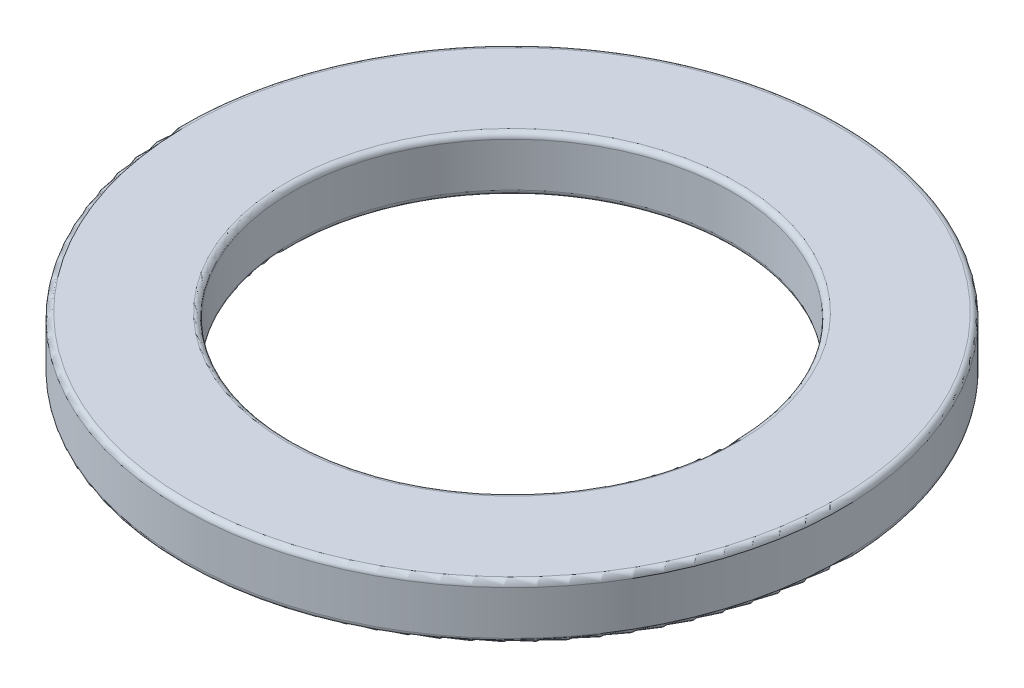
SolidWorks part; units mm, degrees
ref_plane "Front Plane" through (0, 0, 0) normal (0, 0, 1) x (1, 0, 0)
ref_plane "Top Plane" through (0, 0, 0) normal (0, 1, 0) x (1, 0, 0)
ref_plane "Right Plane" through (0, 0, 0) normal (1, 0, 0) x (0, 0, -1)
sketch "Sketch1" plane through (0, 0, 0) normal (0, 1, 0) x (1, 0, 0)
  circle A0 centre (0, 0) radius 30
  circle A1 centre (0, 0) radius 20
  dimension "D1" = 60
  dimension "D2" = 10
extrude "Boss-Extrude1" add sketch "Sketch1" along normal blind 5
fillet "Fillet1" radius 0.5 4 edges at (0, 0, 20) (0, 5, 20) (0, 0, 30) (0, 5, 30)
